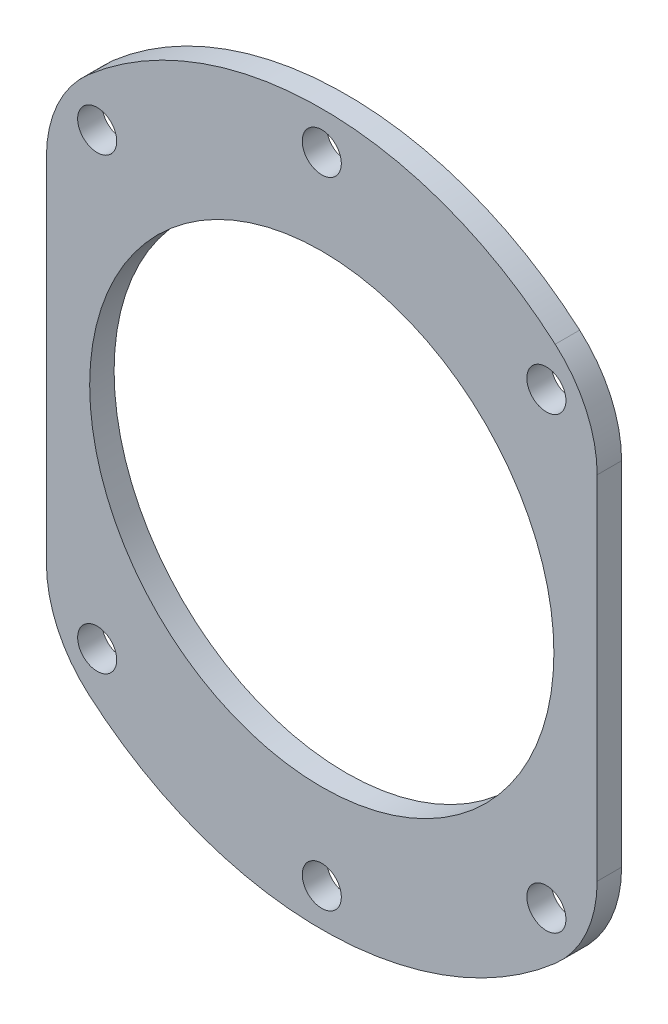
SolidWorks part; units mm, degrees
ref_plane "Front Plane" through (0, 0, 0) normal (0, 0, 1) x (1, 0, 0)
ref_plane "Top Plane" through (0, 0, 0) normal (0, 1, 0) x (1, 0, 0)
ref_plane "Right Plane" through (0, 0, 0) normal (1, 0, 0) x (0, 0, -1)
sketch "Sketch1" plane through (0, 0, 0) normal (0, 0, 1) x (1, 0, 0)
  line L2 (-81.3414, 18.4037) -> (-81.3414, -18.4037)
  line L3 (-36.2586, 18.4037) -> (-36.2586, -18.4037)
  arc A1 (-81.3414, -18.4037) -> (-36.2586, -18.4037) centre (-58.8, 0) ccw construction
  arc A11 (-81.3414, -18.4037) -> (-36.2586, -18.4037) centre (-58.8, 0) ccw
  arc A12 (-36.2586, 18.4037) -> (-81.3414, 18.4037) centre (-58.8, 0) ccw construction
  circle A13 centre (-58.8, 0) radius 19
  arc A14 (-36.2586, 18.4037) -> (-81.3414, 18.4037) centre (-58.8, 0) ccw
  dimension "D1" = 38
extrude "Boss-Extrude1" add sketch "Sketch1" along normal blind 2
sketch "Sketch2" plane through (0, 0, 2) normal (0, 0, 1) x (1, 0, 0)
  circle A0 centre (-58.8, 0) radius 26 construction
  circle A1 centre (-58.8, 26) radius 1.6
  circle A2 centre (-40.4152, 18.3848) radius 1.6
  circle A4 centre (-40.4152, -18.3848) radius 1.6
  circle A5 centre (-58.8, -26) radius 1.6
  circle A6 centre (-77.1848, -18.3848) radius 1.6
  circle A8 centre (-77.1848, 18.3848) radius 1.6
  circle A9 centre (-84.8, 0) radius 1.6 [skipped]
  circle A10 centre (-32.8, 0) radius 1.6 [skipped]
  point P22 (-58.8, 0)
  dimension "D1" = 52
  dimension "D2" = 3.2
  dimension "D3" = 8
extrude "Cut-Extrude1" cut sketch "Sketch2" against normal through all
fillet "Fillet1" radius 10 4 edges at (-81.3414, -18.4037, 1) (-81.3414, 18.4037, 1) (-36.2586, -18.4037, 1) (-36.2586, 18.4037, 1)
